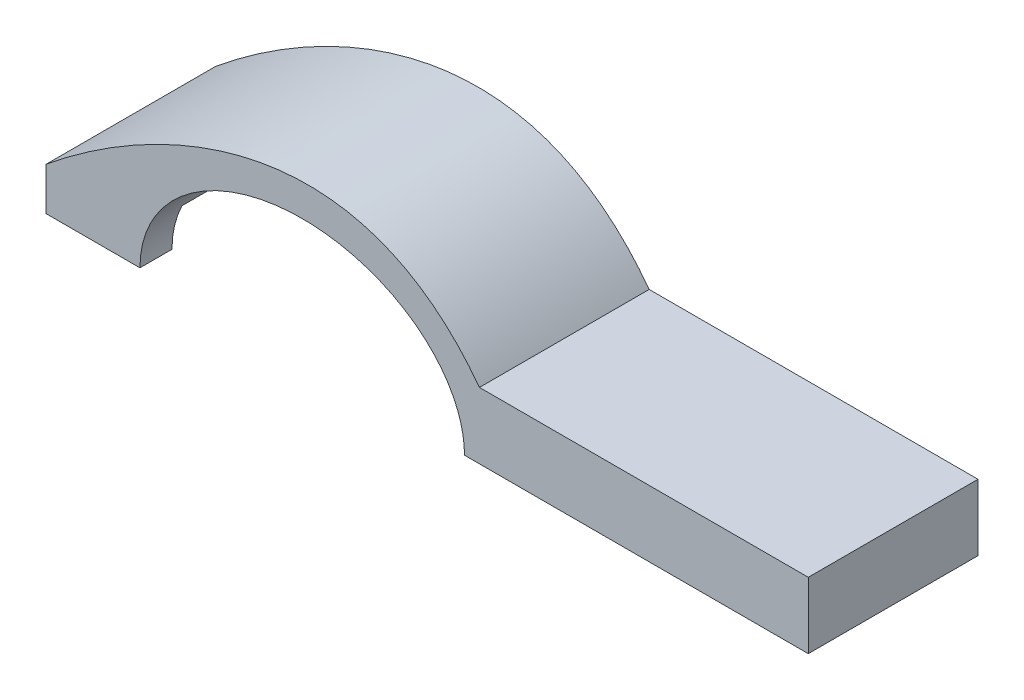
SolidWorks part; units mm, degrees
ref_plane "Front Plane" through (0, 0, 0) normal (0, 0, 1) x (1, 0, 0)
ref_plane "Top Plane" through (0, 0, 0) normal (0, 1, 0) x (1, 0, 0)
ref_plane "Right Plane" through (0, 0, 0) normal (1, 0, 0) x (0, 0, -1)
sketch "Sketch1" plane through (0, 0, 0) normal (0, 0, 1) x (1, 0, 0)
  line L0 (51.0209, -4.3635) -> (34.9209, -4.3635)
  line L1 (51.0209, -4.3635) -> (51.0209, -1.2635)
  line L2 (51.0209, -1.2635) -> (35.6209, -1.2635)
  line L3 (19.7209, -4.3635) -> (15.3209, -4.3635)
  line L4 (15.3209, -4.3635) -> (15.3209, -2.3635)
  line L5 (34.9209, -4.3635) -> (19.7209, -4.3635) construction
  ellipse E0 centre (27.3209, -4.3635) end of major axis (34.9209, -4.3635) minor radius 5.8 (19.7209, -4.3635) -> (34.9209, -4.3635) cw
  spline S0 degree 3 poles (15.3209, -2.3635) (20.7728, 2.1241) (29.9274, 6.3697) (35.6209, -1.2635) knots 0 0 0 0 1 1 1 1
  dimension "D4" = 15.2
  dimension "D3" = 5.8
  dimension "D1" = 3.1
  dimension "D2" = 16.1
  dimension "D5" = 4.4
  dimension "D6" = 2
  dimension "D7" = 1.5
  dimension "D8" = 15.4
extrude "Boss-Extrude1" add sketch "Sketch1" along normal blind 7.95
sketch "Sketch2" plane through (15.3209, 0, 0) normal (-1, 0, 0) x (0, 0, 1)
  line L0 (1.5, -4.3635) -> (1.5, -2.3635)
  line L1 (7.95, -4.3635) -> (0, -4.3635) construction
  line L2 (1.5, -2.3635) -> (6.45, -2.3635)
  line L3 (6.45, -2.3635) -> (6.45, -4.3635)
  line L4 (6.45, -4.3635) -> (1.5, -4.3635)
  line L5 (0, -2.3635) -> (0, -4.3635) construction
  line L6 (7.95, -2.3635) -> (7.95, -4.3635) construction
  dimension "D1" = 1.5
  dimension "D2" = 1.5
  dimension "D3" = 2
extrude "Cut-Extrude1" cut sketch "Sketch2" against normal blind 7.8
sketch "Sketch3" plane through (0, -4.3635, 0) normal (0, -1, 0) x (1, 0, 0)
  line L0 (36.4209, 6.45) -> (36.4209, 1.5)
  line L1 (36.4209, 1.5) -> (49.5209, 1.5)
  line L2 (49.5209, 1.5) -> (49.5209, 6.45)
  line L3 (36.4209, 6.45) -> (49.5209, 6.45)
  line L4 (34.9209, 7.95) -> (51.0209, 7.95) construction
  line L5 (34.9209, 7.95) -> (34.9209, 0) construction
  line L6 (34.9209, 0) -> (51.0209, 0) construction
  line L7 (51.0209, 7.95) -> (51.0209, 0) construction
  dimension "D1" = 1.5
  dimension "D2" = 1.5
  dimension "D3" = 1.5
  dimension "D4" = 1.5
extrude "Cut-Extrude2" cut sketch "Sketch3" against normal blind 2
